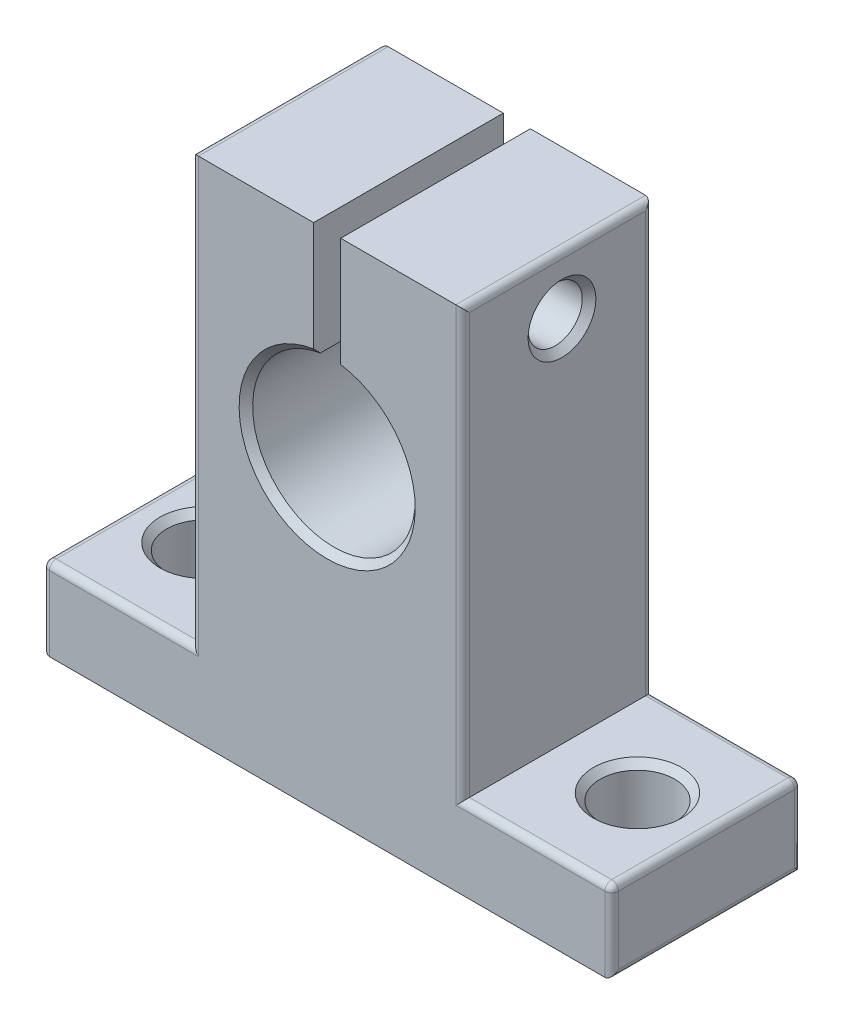
SolidWorks part; units mm, degrees
material "1060 Alloy"
ref_plane "Front Plane" through (0, 0, 0) normal (0, 0, 1) x (1, 0, 0)
ref_plane "Top Plane" through (0, 0, 0) normal (0, 1, 0) x (1, 0, 0)
ref_plane "Right Plane" through (0, 0, 0) normal (1, 0, 0) x (0, 0, -1)
sketch "Sketch1" plane through (0, 0, 0) normal (0, 0, 1) x (1, 0, 0)
  line L0 (0, 0) -> (-50000, 0) construction
  line L1 (0, 0) -> (0, 50000) construction
  line L2 (-21, -3) -> (-21, 3)
  line L3 (-21, 3) -> (-10, 3)
  line L4 (-10, 3) -> (-10, 34.5)
  line L5 (-10, 34.5) -> (-1, 34.5)
  line L6 (10, 34.5) -> (10, 3)
  line L7 (10, 3) -> (21, 3)
  line L8 (21, 3) -> (21, -3)
  line L9 (21, -3) -> (-21, -3)
  line L10 (16, -3) -> (16, 3) construction
  line L11 (-16, -3) -> (-16, 3) construction
  line L12 (-1, 34.5) -> (-1, 25.9161)
  line L13 (1, 34.5) -> (1, 25.9161)
  line L14 (1, 34.5) -> (10, 34.5)
  arc A0 (-1, 25.9161) -> (1, 25.9161) centre (0, 20) ccw
  point P8 (-21, 0)
  point P15 (0, -3)
  point P21 (16, 0)
  dimension "Shaft Diameter" = 12
  dimension "W" = 42
  dimension "P" = 20
  dimension "F" = 37.5
  dimension "G" = 6
  dimension "B" = 32
  dimension "D1" = 2
  dimension "h" = 23
extrude "Boss-Extrude1" add sketch "Sketch1" along normal mid plane 14
sketch "Sketch2" plane through (0, 3, 0) normal (0, 1, 0) x (1, 0, 0)
  line L0 (0, 0) -> (50000, 0) construction
  line L1 (0.3141, 0) -> (-49999.6859, 0) construction
  line L2 (-0.0955, 2.4842) -> (-0.0955, 50002.4842) construction
  circle A0 centre (15.9045, 0) radius 2.75
  circle A1 centre (-16.0955, 0) radius 2.75
  dimension "B" = 32
  dimension "S" = 5.5
extrude "Cut-Extrude1" cut sketch "Sketch2" against normal through all
sketch "Sketch5" plane through (-1, 0, 0) normal (1, 0, 0) x (0, 0, -1)
  line L0 (-7, 30.208) -> (7, 30.208) construction
  line L1 (7, 25.9161) -> (7, 34.5) construction
  line L2 (0, 34.5) -> (0, 25.9161) construction
  line L3 (-7, 34.5) -> (7, 34.5) construction
  line L4 (-7, 25.9161) -> (7, 25.9161) construction
  line L5 (-7, 25.9161) -> (-7, 34.5) construction
  circle A0 centre (0.3307, 30.208) radius 2
  dimension "Clamping bold" = 4
extrude "Cut-Extrude2" cut sketch "Sketch5" against normal through all both and the other way through all
chamfer "Chamfer2" distance 0.5 angle 45 6 edges at (0, 14, -7) (0, 14, 7) (-10, 30.208, -2.3307) (-13.3455, 3, 0) (10, 30.208, 1.6693) (13.1545, 3, 0)
fillet "Fillet2" radius 0.5 18 edges at (21, -3, 0) (21, 0, 7) (21, 3, 0) (21, 0, -7) (-21, 3, 0) (-21, 0, 7) (-21, -3, 0) (-21, 0, -7) (-15.5, 3, -7) (-15.5, 3, 7) (-10, 18.75, 7) (-10, 34.5, 0) (-10, 18.75, -7) (10, 18.75, -7) (10, 18.75, 7) (15.5, 3, 7) (15.5, 3, -7) (10, 34.5, 0)
equation "\"W\"= \"W@Sketch1\"'Width"
equation "\"B\"= \"B@Sketch1\"'between hold"
equation "\"F\"= \"F@Sketch1\"'Hight"
equation "\"P\"= \"P@Sketch1\""
equation "\"G\"= \"G@Sketch1\""
equation "\"Shaft diameter\"= \"Shaft Diameter@Sketch1\""
equation "\"S\"= 5.5'M5"
equation "\"Clamping bold\"= 4'M4"
equation "\"h\"= \"h@Sketch1\""
